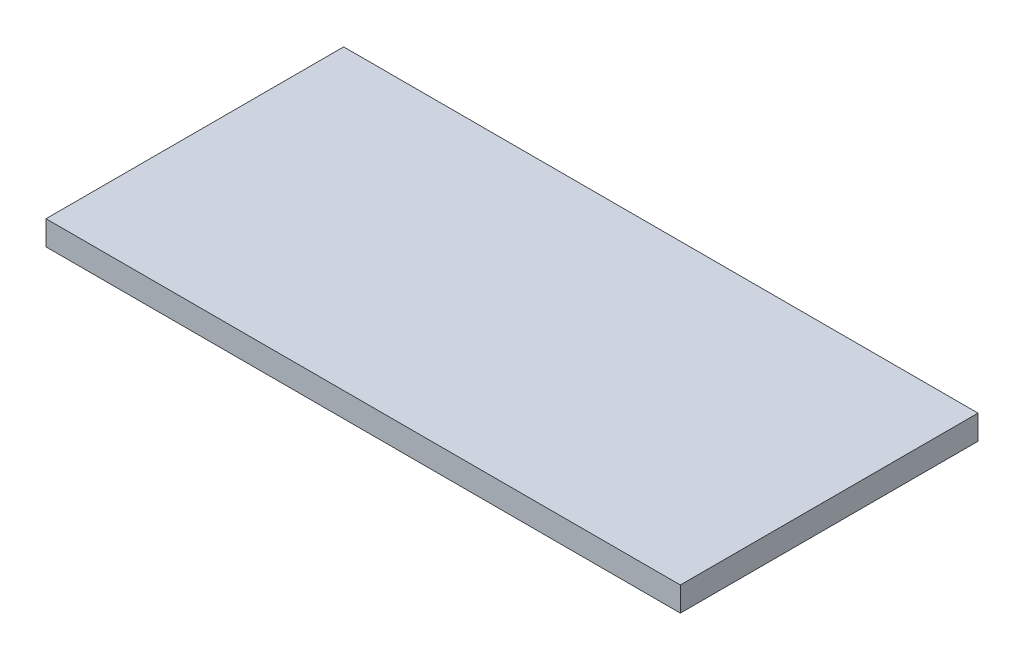
SolidWorks part; units mm, degrees
ref_plane "Front Plane" through (0, 0, 0) normal (0, 0, 1) x (1, 0, 0)
ref_plane "Top Plane" through (0, 0, 0) normal (0, 1, 0) x (1, 0, 0)
ref_plane "Right Plane" through (0, 0, 0) normal (1, 0, 0) x (0, 0, -1)
sketch "Sketch1" plane through (0, 0, 0) normal (0, 1, 0) x (1, 0, 0)
  line L1 (-40.5106, -5.1444) -> (89.4894, -5.1444)
  line L2 (-40.5106, -5.1444) -> (-40.5106, -66.1444)
  line L3 (-40.5106, -66.1444) -> (89.4894, -66.1444)
  line L4 (89.4894, -5.1444) -> (89.4894, -66.1444)
  dimension "D1" = 130
  dimension "D2" = 61
extrude "Boss-Extrude1" add sketch "Sketch1" along normal blind 5
